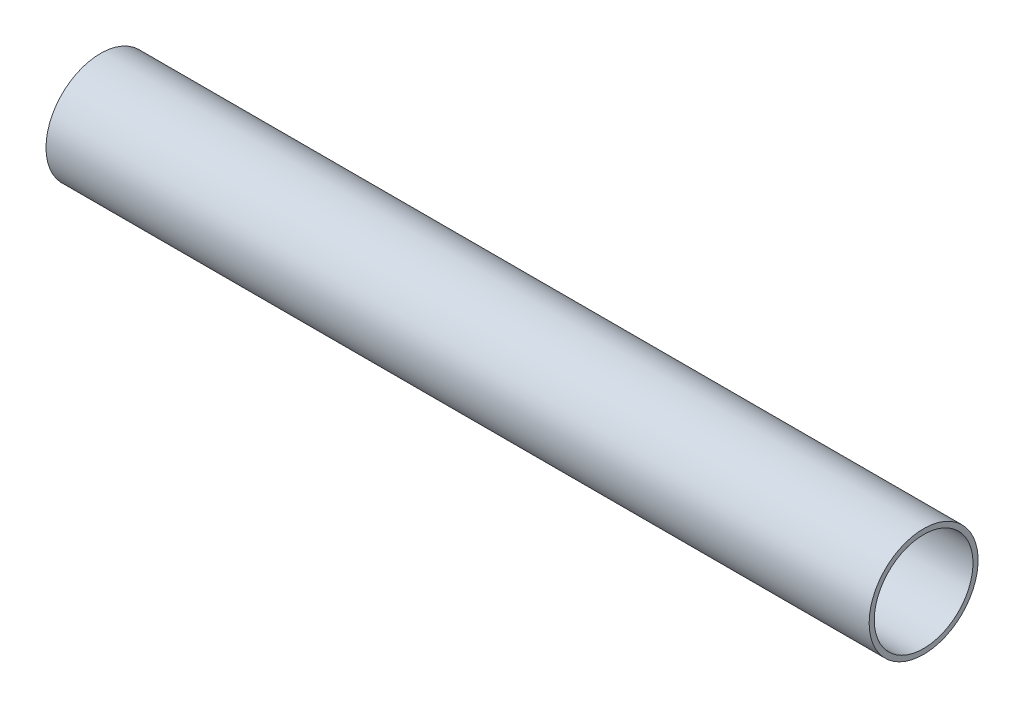
SolidWorks part; units mm, degrees
ref_plane "Front Plane" through (0, 0, 0) normal (0, 0, 1) x (1, 0, 0)
ref_plane "Top Plane" through (0, 0, 0) normal (0, 1, 0) x (1, 0, 0)
ref_plane "Right Plane" through (0, 0, 0) normal (1, 0, 0) x (0, 0, -1)
sketch "Sketch1" plane through (0, 0, 0) normal (0, 0, 1) x (1, 0, 0)
  line L1 (0, 13.5) -> (225.11, 13.5)
  line L4 (0, 13.5) -> (0, 14.9)
  line L5 (0, 14.9) -> (225.11, 14.9)
  line L6 (225.11, 14.9) -> (225.11, 13.5)
  line L7 (0, 0) -> (141.4333, 0) construction
  dimension "D1" = 13.5
  dimension "D2" = 14.9
  dimension "D3" = 225.11
revolve "Revolve1" add sketch "Sketch1" angle 360 about L7
